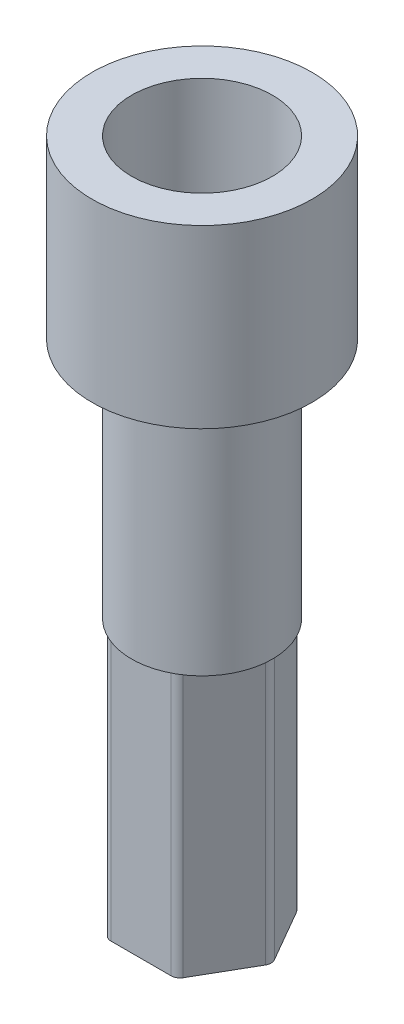
SolidWorks part; units mm, degrees
ref_plane "Front Plane" through (0, 0, 0) normal (0, 0, 1) x (1, 0, 0)
ref_plane "Top Plane" through (0, 0, 0) normal (0, 1, 0) x (1, 0, 0)
ref_plane "Right Plane" through (0, 0, 0) normal (1, 0, 0) x (0, 0, -1)
sketch "Sketch1" plane through (0, 0, 0) normal (1, 0, 0) x (0, 0, -1)
  line L0 (0, 0) -> (0, 41.2274) construction
  line L1 (0, 0) -> (4.064, 0)
  line L2 (4.064, 0) -> (4.064, 13.97)
  line L3 (4.064, 29.21) -> (6.35, 29.21)
  line L4 (6.35, 29.21) -> (6.35, 39.37)
  line L5 (6.35, 39.37) -> (0, 39.37)
  line L6 (0, 39.37) -> (0, 0)
  line L8 (4.064, 13.97) -> (4.064, 29.21)
  dimension "D2" = 6.35
  dimension "D3" = 10.16
  dimension "D4" = 39.37
  dimension "D5" = 4.064
  dimension "D6" = 15.24
revolve "Revolve1" add sketch "Sketch1" angle 360 about L0
sketch "Sketch2" plane through (0, 39.37, 0) normal (0, 1, 0) x (1, 0, 0)
  circle A0 centre (0, 0) radius 4.064
  dimension "D1" = 8.128
extrude "Cut-Extrude1" cut sketch "Sketch2" against normal blind 8.382
sketch "Sketch3" plane through (0, 0, 0) normal (0, -1, 0) x (1, 0, 0)
  line L1 (2.032, 3.5195) -> (-2.032, 3.5195)
  line L2 (-2.032, 3.5195) -> (-4.064, 0)
  line L3 (-4.064, 0) -> (-2.032, -3.5195)
  line L4 (-2.032, -3.5195) -> (2.032, -3.5195)
  line L5 (2.032, -3.5195) -> (4.064, 0)
  line L6 (4.064, 0) -> (2.032, 3.5195)
  circle A0 centre (0, 0) radius 3.5195 construction
  circle A1 centre (0, 0) radius 4.064
  circle A2 centre (0, 0) radius 4.064 construction
  circle M10 centre (0, 0) radius 4.064
extrude "Cut-Extrude3" cut sketch "Sketch3" against normal blind 15.24 contours L1 M10 | L6 M10 | L5 M10 | L4 M10 | L3 M10 | L2 M10
fillet "Fillet2" radius 0.508 6 edges at (-4.064, 7.62, 0) (-2.032, 7.62, -3.5195) (-2.032, 7.62, 3.5195) (2.032, 7.62, -3.5195) (4.064, 7.62, 0) (2.032, 7.62, 3.5195)
